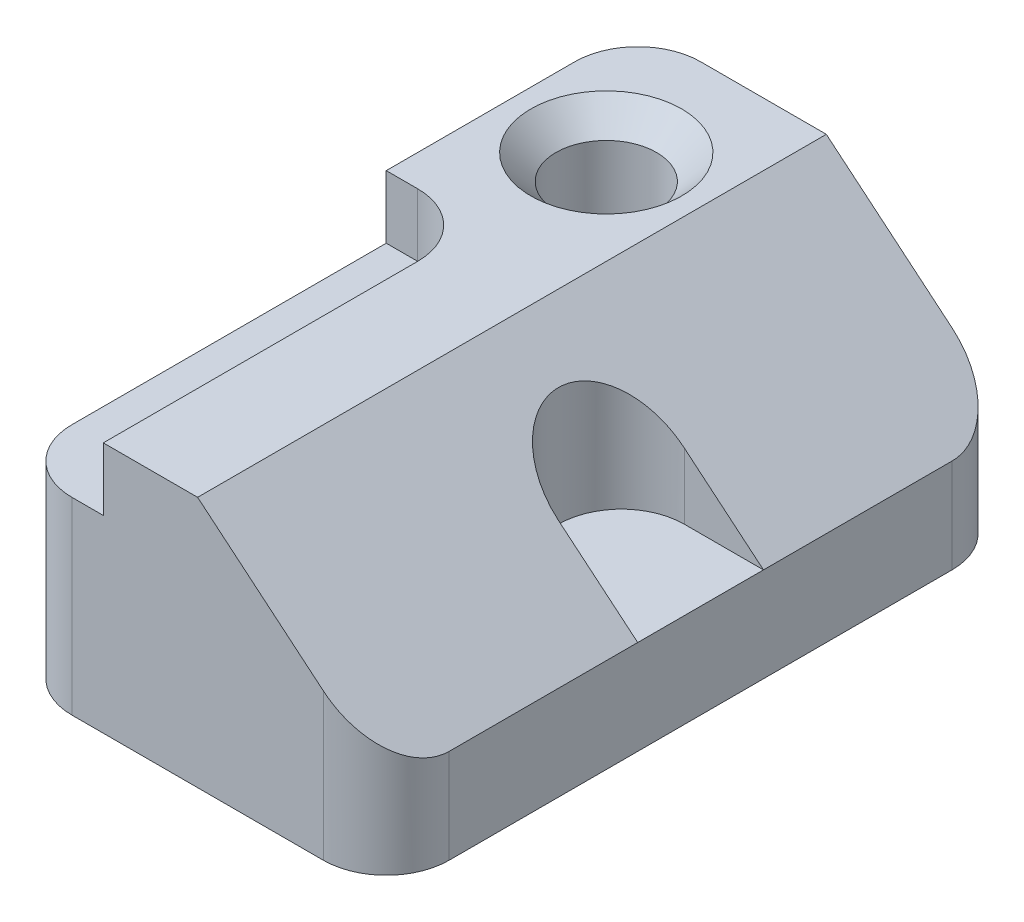
SolidWorks part; units mm, degrees
material "Malleable Cast Iron"
ref_plane "Front Plane" through (0, 0, 0) normal (0, 0, 1) x (1, 0, 0)
ref_plane "Top Plane" through (0, 0, 0) normal (0, 1, 0) x (1, 0, 0)
ref_plane "Right Plane" through (0, 0, 0) normal (1, 0, 0) x (0, 0, -1)
sketch "Sketch1" plane through (0, 0, 0) normal (0, 0, 1) x (1, 0, 0)
  line L0 (0, 50.8) -> (0, 0)
  line L1 (0, 0) -> (76.2, 0)
  line L2 (0, 50.8) -> (38.1, 50.8)
  line L3 (76.2, 0) -> (76.2, 19.05)
  line L4 (76.2, 19.05) -> (38.1, 50.8)
  dimension "D1" = 76.2
  dimension "D2" = 50.8
  dimension "D3" = 38.1
  dimension "D4" = 19.05
extrude "Boss-Extrude1" add sketch "Sketch1" along normal blind 127
sketch "Sketch2" plane through (0, 50.8, 0) normal (0, 1, 0) x (1, 0, 0)
  line L0 (0, -127) -> (0, 0) construction
  line L2 (38.1, 0) -> (0, 0) construction
  circle A0 centre (19.0445, -25.4) radius 10.16
  dimension "D1" = 20.32
  dimension "D2" = 19.0445
  dimension "D3" = 25.4
extrude "Cut-Extrude1" cut sketch "Sketch2" against normal through all
chamfer "Chamfer1" distance 5.08 angle 45 1 edges at (19.0445, 50.8, 35.56)
sketch "Sketch3" plane through (0, 50.8, 0) normal (0, 1, 0) x (1, 0, 0)
  line L5 (0, -127) -> (19.05, -127)
  line L6 (0, -127) -> (0, -50.8)
  line L7 (0, -50.8) -> (19.05, -50.8)
  line L8 (19.05, -127) -> (19.05, -50.8)
  dimension "D1" = 76.2
  dimension "D2" = 19.05
extrude "Cut-Extrude2" cut sketch "Sketch3" against normal blind 12.7
fillet "Fillet1" radius 12.7 1 edges at (19.05, 44.45, 50.8)
sketch "Sketch8" plane through (0, 50.8, 0) normal (0, 1, 0) x (1, 0, 0)
  line L0 (76.2, -50.8) -> (60.198, -50.8)
  line L1 (76.2, -127) -> (76.2, 0) construction
  line L2 (60.198, -76.2) -> (76.2, -76.2)
  line L3 (76.2, -63.5) -> (31.4461, -63.5) construction
  line L4 (76.2, -50.8) -> (76.2, -76.2)
  arc A0 (60.198, -50.8) -> (60.198, -76.2) centre (60.198, -63.5) ccw
  dimension "D2" = 12.7
  dimension "D1" = 16.002
extrude "Cut-Extrude4" cut sketch "Sketch8" against normal up to vertex (31.75 mm away) contours L4 L2 A0 L0
fillet "Fillet2" radius 12.7 4 edges at (76.2, 9.525, 0) (0, 25.4, 0) (0, 19.05, 127) (76.2, 9.525, 127)
